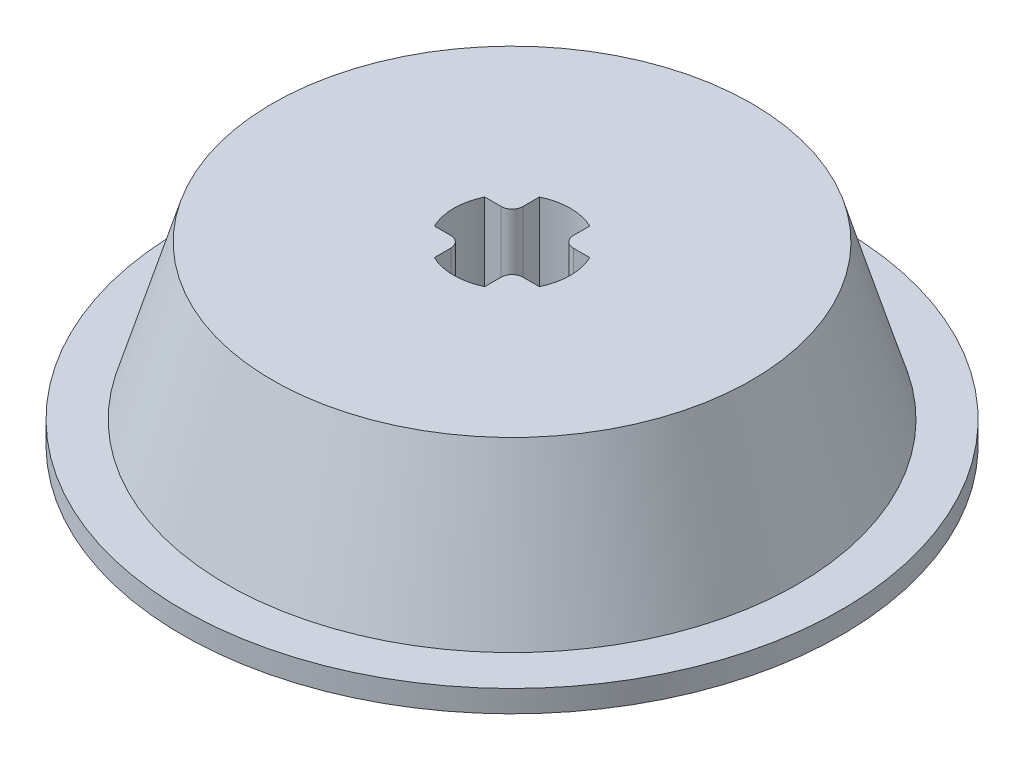
SolidWorks part; units mm, degrees
ref_plane "Front Plane" through (0, 0, 0) normal (0, 0, 1) x (1, 0, 0)
ref_plane "Top Plane" through (0, 0, 0) normal (0, 1, 0) x (1, 0, 0)
ref_plane "Right Plane" through (0, 0, 0) normal (1, 0, 0) x (0, 0, -1)
sketch "Sketch1" plane through (0, 0, 0) normal (0, 1, 0) x (1, 0, 0)
  circle A0 centre (0, 0) radius 13
  dimension "D1" = 26
extrude "Boss-Extrude1" add sketch "Sketch1" along normal blind 7
sketch "Sketch2" plane through (0, 0, 0) normal (1, 0, 0) x (0, 0, -1)
  line L0 (-13, 0) -> (-10.9079, 7)
  line L1 (13, 7) -> (-13, 7) construction
  line L2 (-10.9079, 7) -> (-13, 7)
  line L3 (-13, 7) -> (-13, 0)
  line L4 (0, 0) -> (0, 50000) construction
  line L5 (-13, 0) -> (13, 0) construction
  point P11 (0, 0)
  dimension "D1" = 16.64
revolve "Cut-Revolve1" cut sketch "Sketch2" angle 360 about L4
sketch "Sketch3" plane through (0, 0, 0) normal (0, -1, 0) x (-1, 0, 0)
  circle A0 centre (0, 0) radius 15
  dimension "D1" = 30
extrude "Boss-Extrude2" add sketch "Sketch3" along normal blind 1
sketch "Sketch4" plane through (0, -1, 0) normal (0, -1, 0) x (1, 0, 0)
  line L0 (1.145, -2.3899) -> (1.145, 2.3899)
  line L1 (-1.145, -2.3899) -> (-1.145, 2.3899)
  line L2 (0, 0) -> (35355.3391, 35355.3391) construction
  line L3 (0.8543, 0) -> (50000.8543, 0) construction
  line L4 (-2.3899, 1.145) -> (2.3899, 1.145)
  line L5 (-2.3899, -1.145) -> (2.3899, -1.145)
  circle A0 centre (0, 0) radius 2.65
  dimension "D1" = 5.3
  dimension "D2" = 2.29
  dimension "D3" = 45
extrude "Cut-Extrude1" cut sketch "Sketch4" against normal through all contours L1 L5 L0 L4 | L4 A0 L5 L1 | L0 A0 L1 L4 | L5 A0 L4 L0 | L1 A0 L0 L5
fillet "Fillet1" radius 0.5 4 edges at (1.145, 3, 1.145) (1.145, 3, -1.145) (-1.145, 3, -1.145) (-1.145, 3, 1.145)
sketch "Sketch5" plane through (0, 7, 0) normal (0, 1, 0) x (1, 0, 0)
  line L0 (-1.9033, 1) -> (1.9033, 1)
  circle A0 centre (0, 0) radius 2.15
  dimension "D1" = 4.3
  dimension "D2" = 1
extrude "Cut-Extrude2" [suppressed] cut sketch "Sketch5" against normal through all contours L0 A0
